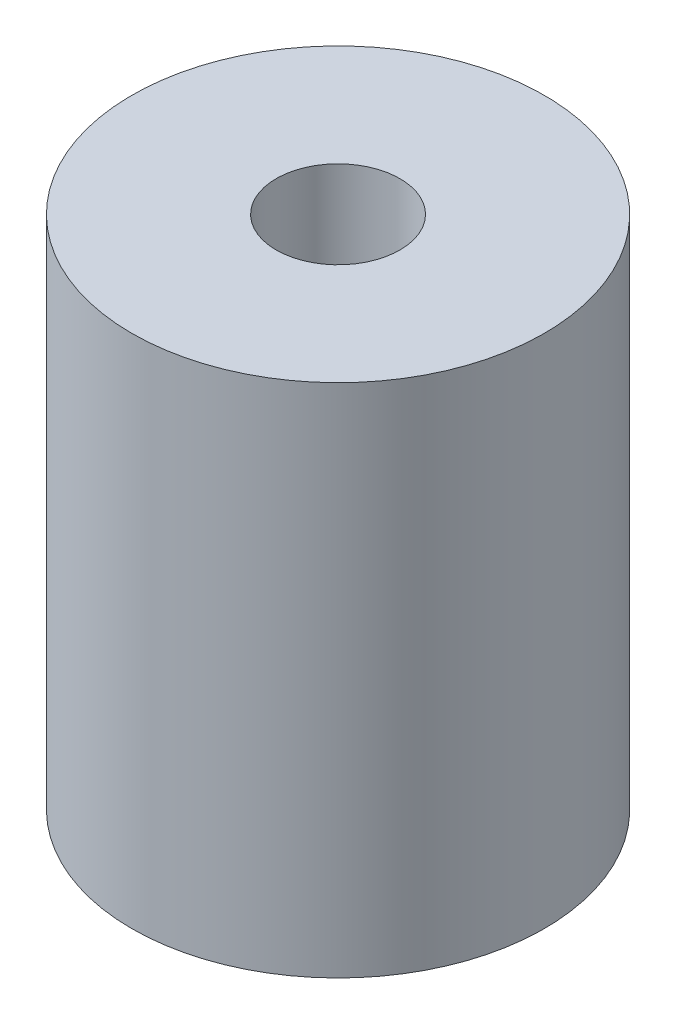
SolidWorks part; units mm, degrees
material "1060 Alloy"
ref_plane "Front Plane" through (0, 0, 0) normal (0, 0, 1) x (1, 0, 0)
ref_plane "Top Plane" through (0, 0, 0) normal (0, 1, 0) x (1, 0, 0)
ref_plane "Right Plane" through (0, 0, 0) normal (1, 0, 0) x (0, 0, -1)
sketch "Sketch1" plane through (0, 0, 0) normal (0, 1, 0) x (1, 0, 0)
  circle A0 centre (0, 0) radius 10
  dimension "D1" = 20
extrude "Boss-Extrude1" add sketch "Sketch1" along normal blind 25
sketch "Sketch3" plane through (0, 25, 0) normal (0, 1, 0) x (1, 0, 0)
  circle A0 centre (0, 0) radius 3
  dimension "D1" = 6
extrude "Cut-Extrude1" cut sketch "Sketch3" against normal through all
sketch "Sketch4" plane through (0, 0, 0) normal (0, -1, 0) x (1, 0, 0)
  circle A0 centre (0, 0) radius 4.5
  dimension "D1" = 9
extrude "Cut-Extrude2" cut sketch "Sketch4" against normal blind 10
